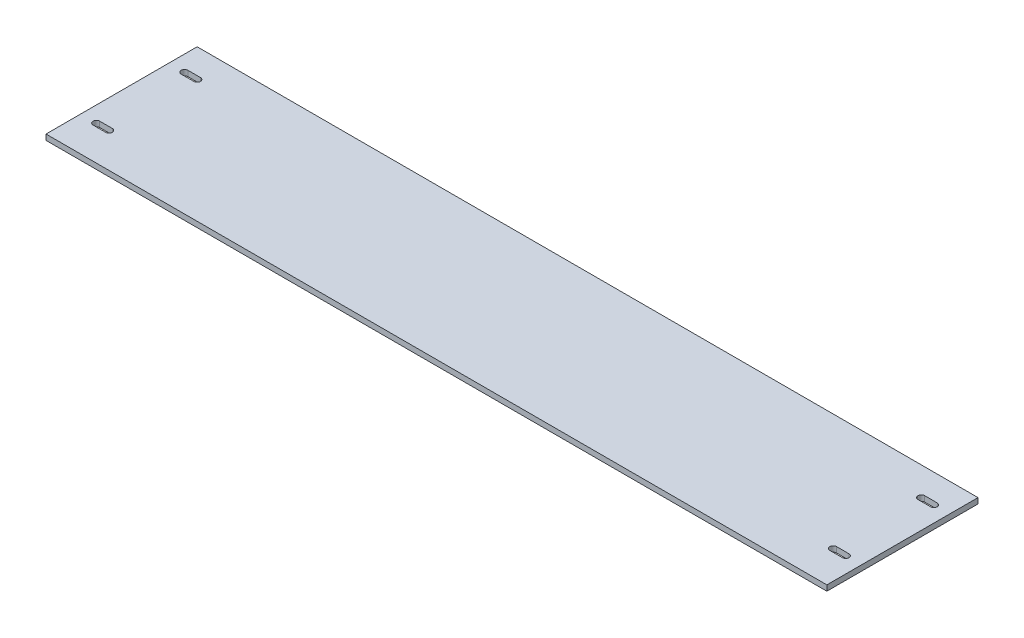
SolidWorks part; units mm, degrees
material "PC High Viscosity"
ref_plane "Front" through (0, 0, 0) normal (0, 0, 1) x (1, 0, 0)
ref_plane "Top" through (0, 0, 0) normal (0, 1, 0) x (1, 0, 0)
ref_plane "Right" through (0, 0, 0) normal (1, 0, 0) x (0, 0, -1)
sketch "Sketch1" plane through (0, 0, 0) normal (0, 1, 0) x (1, 0, 0)
  line L0 (15.875, 34.925) -> (28.575, 34.925) construction
  line L1 (0, 0) -> (787.4, 0)
  line L2 (0, 0) -> (0, 152.4)
  line L3 (0, 152.4) -> (787.4, 152.4)
  line L4 (787.4, 0) -> (787.4, 152.4)
  line L5 (15.875, 38.3032) -> (28.575, 38.3032)
  line L6 (15.875, 31.5468) -> (28.575, 31.5468)
  line L7 (22.225, 34.925) -> (22.225, 123.825) construction
  line L8 (15.875, 123.825) -> (28.575, 123.825) construction
  line L9 (15.875, 127.2032) -> (28.575, 127.2032)
  line L10 (15.875, 120.4468) -> (28.575, 120.4468)
  line L11 (22.225, 123.825) -> (66.675, 123.825) construction
  line L12 (66.675, 123.825) -> (66.675, 34.925) construction
  line L13 (66.675, 34.925) -> (22.225, 34.925) construction
  line L14 (60.325, 123.825) -> (73.025, 123.825) construction
  line L15 (60.325, 127.2032) -> (73.025, 127.2032) construction
  line L16 (60.325, 120.4468) -> (73.025, 120.4468) construction
  line L17 (60.325, 34.925) -> (73.025, 34.925) construction
  line L18 (60.325, 38.3032) -> (73.025, 38.3032) construction
  line L19 (60.325, 31.5468) -> (73.025, 31.5468) construction
  line L20 (765.175, 123.825) -> (765.175, 34.925) construction
  line L21 (771.525, 123.825) -> (758.825, 123.825) construction
  line L22 (771.525, 120.4468) -> (758.825, 120.4468)
  line L23 (771.525, 127.2032) -> (758.825, 127.2032)
  line L24 (771.525, 34.925) -> (758.825, 34.925) construction
  line L25 (771.525, 31.5468) -> (758.825, 31.5468)
  line L26 (771.525, 38.3032) -> (758.825, 38.3032)
  arc A0 (15.875, 38.3032) -> (15.875, 31.5468) centre (15.875, 34.925) ccw
  arc A1 (28.575, 31.5468) -> (28.575, 38.3032) centre (28.575, 34.925) ccw
  arc A2 (15.875, 127.2032) -> (15.875, 120.4468) centre (15.875, 123.825) ccw
  arc A3 (28.575, 120.4468) -> (28.575, 127.2032) centre (28.575, 123.825) ccw
  arc A4 (60.325, 127.2032) -> (60.325, 120.4468) centre (60.325, 123.825) ccw construction
  arc A5 (73.025, 120.4468) -> (73.025, 127.2032) centre (73.025, 123.825) ccw construction
  arc A6 (60.325, 38.3032) -> (60.325, 31.5468) centre (60.325, 34.925) ccw construction
  arc A7 (73.025, 31.5468) -> (73.025, 38.3032) centre (73.025, 34.925) ccw construction
  arc A8 (771.525, 120.4468) -> (771.525, 127.2032) centre (771.525, 123.825) ccw
  arc A9 (758.825, 127.2032) -> (758.825, 120.4468) centre (758.825, 123.825) ccw
  arc A10 (771.525, 31.5468) -> (771.525, 38.3032) centre (771.525, 34.925) ccw
  arc A11 (758.825, 38.3032) -> (758.825, 31.5468) centre (758.825, 34.925) ccw
  point P7 (22.225, 34.925)
  point P13 (22.225, 123.825)
  point P25 (66.675, 123.825)
  point P31 (66.675, 34.925)
  point P40 (765.175, 123.825)
  point P47 (765.175, 34.925)
  dimension "D1" = 6.7564
  dimension "D2" = 34.925
  dimension "D3" = 12.7
  dimension "D4" = 22.225
  dimension "D5" = 28.575
  dimension "D6" = 152.4
  dimension "D7" = 44.45
  dimension "D8" = 22.225
  dimension "D9" = 698.5
extrude "Boss-Extrude1" add sketch "Sketch1" along normal blind 5.588
fillet "Fillet1" [suppressed] radius 3.175
sketch "Sketch2" plane through (0, 5.588, 0) normal (0, 1, 0) x (1, 0, 0)
  line L0 (0, 76.2) -> (787.4, 76.2) construction
  line L1 (0, 152.4) -> (0, 0) construction
  line L2 (787.4, 0) -> (787.4, 152.4) construction
  line L3 (787.4, 152.4) -> (0, 152.4) construction
  line L4 (133.35, 25.4) -> (698.5, 25.4) construction
  line L5 (133.35, 25.4) -> (133.35, 127) construction
  line L6 (133.35, 127) -> (698.5, 127) construction
  line L7 (698.5, 25.4) -> (698.5, 127) construction
  line L8 (133.35, 25.4) -> (698.5, 127) construction
  line L9 (133.35, 127) -> (698.5, 25.4) construction
  circle A1 centre (133.35, 25.4) radius 3.3782
  circle A2 centre (698.5, 25.4) radius 3.3782
  point P6 (415.925, 76.2)
  dimension "D2" = 6.7564
  dimension "D1" = 88.9
  dimension "D3" = 25.4
  dimension "D4" = 565.15
extrude "Cut-Extrude1" [suppressed] cut sketch "Sketch2" against normal through all
